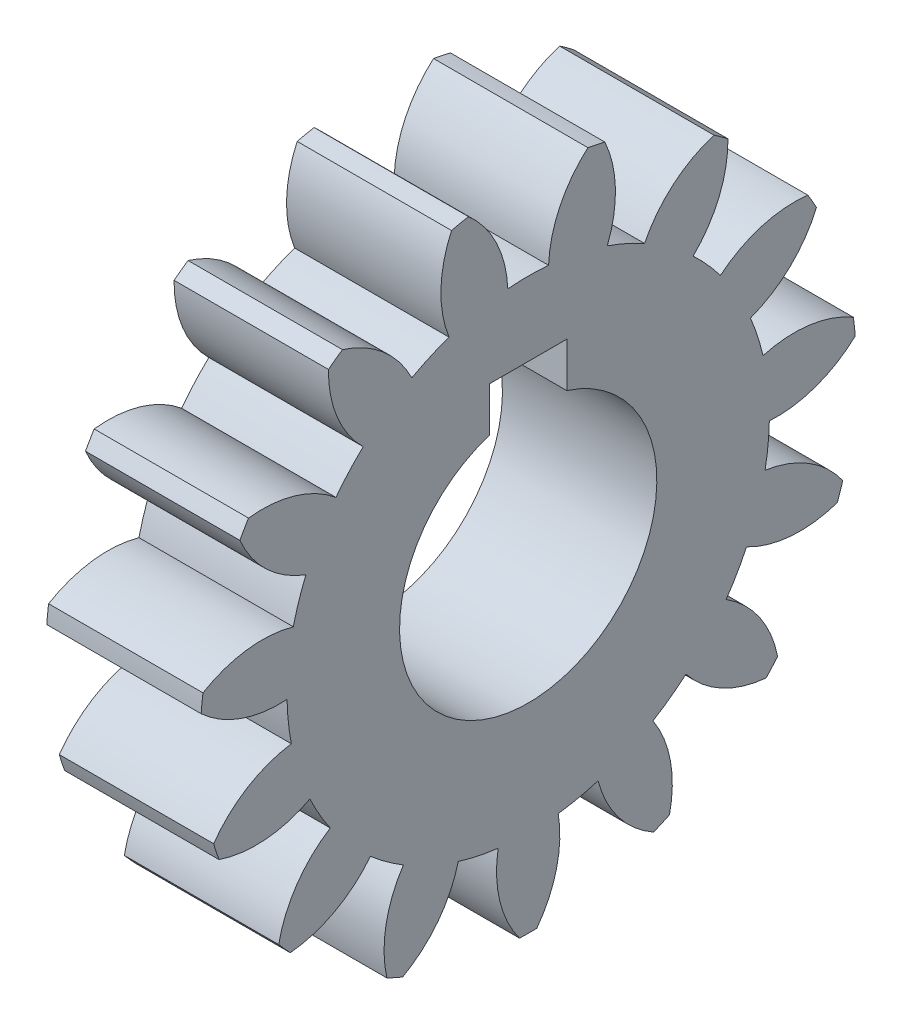
SolidWorks part; units mm, degrees
ref_plane "Plane1" through (0, 0, 0) normal (0, 0, 1) x (1, 0, 0)
ref_plane "Plane2" through (0, 0, 0) normal (0, 1, 0) x (1, 0, 0)
ref_plane "Plane3" through (0, 0, 0) normal (1, 0, 0) x (0, 0, -1)
other "Configuration Table"
sketch "HoldingSke" plane through (0, 0, 0) normal (0, 1, 0) x (1, 0, 0)
  line L0 (0, 0) -> (0.322, -0.0863)
  line L1 (-15, 0) -> (100, 0) construction
  line L2 (0, 0) -> (-2.1039, 2.3779)
  line L3 (0, 0) -> (-11.863, 4.5341)
  line L4 (0, 0) -> (8.3417, 2.2352)
  line L5 (0, 0) -> (-46.8476, -17.4728)
  line L6 (0, 0) -> (-9.9476, -6.7116)
  line L7 (-2.1039, 2.3779) -> (8.6586, 51.2059)
  line L8 (-76.2, 54.61) -> (-73.4, 54.61)
  line L9 (-71.009, 38.7566) -> (-53.1078, 45.2721)
  line L10 (-76.2, 71.12) -> (104.1128, 71.12)
  line L11 (0, 0) -> (-12, 0)
  line L12 (-76.2, 101.6) -> (-76.093, 101.6)
  line L13 (24.9733, 27.94) -> (52.9518, 28.4284)
  line L14 (24.9733, 27.94) -> (24.9743, 27.94)
  line L15 (24.9733, 27.94) -> (100.4006, 29.5858)
  line L16 (-63.627, -3) -> (-12.827, -3)
  circle A0 centre (0, 0) radius 10
  circle A1 centre (0, 0) radius 18.749
  circle A2 centre (0, 0) radius 37.5
  circle A3 centre (0, 0) radius 10
  dimension "MHD" = 37.498
  dimension "Hub_dia" = 75
  dimension "Bore" = 20
  dimension "MBD" = 20
  dimension "Num_teeth" = 15
  dimension "Pitch" = 0.3333
  dimension "Overall_len" = 50
  dimension "Show_teeth" = 15
  dimension "Thickness" = 12
  dimension "OAL" = 50.0001
  dimension "T_dim" = 2.8
  dimension "Ap" = 20
  dimension "H" = 19.05
  dimension "Pitch_radius" = 180.3128
  dimension "Width" = 12
  dimension "Backlash" = 0.107
  dimension "Addendum_fac" = 1
  dimension "Dedendum_fac" = 1.25
  dimension "Clearance_fac" = 0.25
  dimension "Dedendum_add" = 0.001
  dimension "Module" = 3
sketch "BasProSke" plane through (0, 0, 0) normal (0, 1, 0) x (1, 0, 0)
  line L0 (-10, 0) -> (60, 0) construction
  line L1 (0, 0) -> (0, 25.5)
  line L2 (0, 0) -> (12, 0)
  line L3 (12, 0) -> (12, 25.5)
  line L4 (12, 25.5) -> (0, 25.5)
  dimension "Thickness" = 12
  dimension "Diameter" = 51
revolve "Base-Revolve" add sketch "BasProSke" angle 360 about L0
sketch "TooCutSke" plane through (0, 0, 0) normal (1, 0, 0) x (0, 0, -1)
  line L1 (0, 0) -> (0, 107) construction
  line L2 (0, 0) -> (-2.539, 22.3563) construction
  line L3 (0, 0) -> (-9.3126, 43.8125) construction
  line L4 (-2.539, 22.3563) -> (-4.6563, 21.9062) construction
  arc A0 (1.5846, 18.6819) -> (-1.5846, 18.6819) centre (0, 0) ccw
  arc A1 (4.6669, 25.0951) -> (-4.6669, 25.0951) centre (0, 0) ccw
  circle A2 centre (0, 0) radius 22.5 construction
  circle A3 centre (0, 0) radius 21.1431 construction
  arc A4 (-1.5846, 18.6819) -> (-4.6669, 25.0951) centre (-10.5768, 18.3074) ccw
  arc A5 (4.6669, 25.0951) -> (1.5846, 18.6819) centre (10.5768, 18.3074) ccw
  dimension "Root_dia" = 37.498
  dimension "Overcut_dia" = 51.0508
  dimension "Pitch_dia" = 45
  dimension "Base_dia" = 42.2862
  dimension "Flank_rad" = 9
  dimension "Half_ang" = 12
  dimension "Half_CT" = 2.1646
extrude "ToothCut" cut sketch "TooCutSke" along normal through all
fillet "Breaks" [suppressed] radius 0.06
fillet "RootFillets" [suppressed] radius 0.751
pattern_circular "TeethCuts" count 15 every 24 about axis through (-10, 0, 0) along (1, 0, 0) of "ToothCut", "RootFillets", "Breaks"
sketch "HubNeaOneSke" plane through (0, 0, 0) normal (-1, 0, 0) x (0, 0, 1)
  circle A0 centre (0, 0) radius 18.749
  dimension "Diameter" = 37.498
extrude "HubNearOne" [suppressed] add sketch "HubNeaOneSke" along normal blind 38.0001
sketch "HubNeaBotSke" plane through (0, 0, 0) normal (-1, 0, 0) x (0, 0, 1)
  circle A0 centre (0, 0) radius 18.749
  dimension "Diameter" = 37.498
extrude "HubNearBoth" [suppressed] add sketch "HubNeaBotSke" along normal blind 19
ref_plane "FarPln" through (12, 0, 0) normal (1, 0, 0) x (0, 0, -1)
sketch "HubFarSke" plane through (12, 0, 0) normal (1, 0, 0) x (0, 0, -1)
  circle A0 centre (0, 0) radius 18.749
  dimension "Diameter" = 37.498
extrude "HubFar" [suppressed] add sketch "HubFarSke" along normal blind 19
sketch "BorSke" plane through (0, 0, 0) normal (1, 0, 0) x (0, 0, -1)
  circle A0 centre (0, 0) radius 10
  dimension "Diameter" = 20
extrude "Bore" cut sketch "BorSke" along normal mid plane 100.0001
sketch "KeySke" plane through (0, 0, 0) normal (1, 0, 0) x (0, 0, -1)
  line L0 (-3, 0) -> (-3, 12.8)
  line L1 (-3, 12.8) -> (3, 12.8)
  line L2 (3, 12.8) -> (3, 0)
  line L3 (0, 0) -> (0, 34) construction
  line L4 (-3, 0) -> (3, 0)
  dimension "Offset" = 12.8
  dimension "Width" = 6
extrude "Keyway" [suppressed] cut sketch "KeySke" along normal mid plane 100.0001
pattern_circular "Keyway2" [suppressed] count 2 every 90 about axis through (-10, 0, 0) along (1, 0, 0)
sketch "Sketch1" plane through (0, 0, 0) normal (1, 0, 0) x (0, 0, -1)
  line L0 (0, 0) -> (0, 24.1107) construction
  line L2 (-3, 7) -> (3, 7)
  line L3 (-3, 7) -> (-3, 13)
  line L4 (-3, 13) -> (3, 13)
  line L5 (3, 7) -> (3, 13)
  line L6 (-3, 7) -> (3, 13) construction
  line L7 (-3, 13) -> (3, 7) construction
  circle A0 centre (0, 0) radius 10 construction
  point P3 (0, 10)
  dimension "D1" = 6
  dimension "D2" = 6
extrude "Cut-Extrude1" cut sketch "Sketch1" along normal through all both
equation "' \"Module@HoldingSke\" = 6.35"
equation "' \"Num_teeth@HoldingSke\" = 12"
equation "' \"Ap@HoldingSke\" =  20"
equation "' \"Ap@HoldingSke\" = 20"
equation "' \"Width@HoldingSke\" = 0.5 * 25.4"
equation "' \"Hub_dia@HoldingSke\"= 1 * 25.4"
equation "' \"Hub_dia@HoldingSke\" = 1 * 25.4"
equation "' \"Overall_len@HoldingSke\" = 1.0 * 25.4"
equation "' \"Bore@HoldingSke\" = 0.75 * 25.4"
equation "' \"T_dim@HoldingSke\" = 0.1 * 25.4"
equation "' \"Width@KeySke\" = 0.25 * 25.4"
equation "' \"Show_teeth@HoldingSke\" = 13"
equation "' \"Backlash@HoldingSke\" = 0.009 * 25.4"
equation "' \"Addendum_fac@HoldingSke\" = 1.0"
equation "' \"Dedendum_fac@HoldingSke\" = 1.25"
equation "' \"Dedendum_add@HoldingSke\" = 0.00005 * 25.4"
equation "' \"Clearance_fac@HoldingSke\" = 0.25"
equation "\"Pitch@HoldingSke\" = 1 / \"Module@HoldingSke\""
equation "\"Overcut_dia@TooCutSke\" = (\"Num_teeth@HoldingSke\" + 2 * \"Addendum_fac@HoldingSke\") / \"Pitch@HoldingSke\" + 0.002 * 25.4"
equation "\"Pitch_dia@TooCutSke\" = \"Num_teeth@HoldingSke\" / \"Pitch@HoldingSke\""
equation "\"Base_dia@TooCutSke\" = \"Num_teeth@HoldingSke\" / \"Pitch@HoldingSke\" * cos((\"Ap@HoldingSke\"  * 3.14159265 / 180))"
equation "\"Root_dia@TooCutSke\" = (\"Num_teeth@HoldingSke\" + 2) / \"Pitch@HoldingSke\" - 2 * (\"Addendum_fac@HoldingSke\" + \"Dedendum_fac@HoldingSke\") / \"Pitch@HoldingSke\" - \"Dedendum_add@HoldingSke\" * 2"
equation "\"Half_ang@TooCutSke\" = 180 / \"Num_teeth@HoldingSke\""
equation "\"Half_CT@TooCutSke\" = \"Num_teeth@HoldingSke\" / \"Pitch@HoldingSke\" * sin((3.14159265 / 2 / \"Num_teeth@HoldingSke\")) / 2 - 7 * \"Backlash@HoldingSke\" / 4"
equation "\"Flank_rad@TooCutSke\" = \"Num_teeth@HoldingSke\" / \"Pitch@HoldingSke\" / 5"
equation "\"Radius@RootFillets\" = \"Clearance_fac@HoldingSke\" / \"Pitch@HoldingSke\" + \"Dedendum_add@HoldingSke\""
equation "\"Break_rad@Breaks\" = 0.02 / \"Pitch@HoldingSke\""
equation "\"Thickness@HoldingSke\" = \"Width@HoldingSke\""
equation "\"OAL@HoldingSke\" = \"Thickness@HoldingSke\""
equation "\"MHD@HoldingSke\" = (\"Num_teeth@HoldingSke\" + 2) / \"Pitch@HoldingSke\" - 2 * (\"Addendum_fac@HoldingSke\" + \"Dedendum_fac@HoldingSke\")  / \"Pitch@HoldingSke\" - \"Dedendum_add@HoldingSke\" * 2"
equation "\"MBD@HoldingSke\" = (\"Num_teeth@HoldingSke\" + 2) / \"Pitch@HoldingSke\" - 2 * (\"Addendum_fac@HoldingSke\" + \"Dedendum_fac@HoldingSke\")  / \"Pitch@HoldingSke\" - \"Dedendum_add@HoldingSke\" * 2 - 0.002 * 25.4"
equation "\"MHD@HoldingSke\" = ((sgn( \"MHD@HoldingSke\" - \"Hub_dia@HoldingSke\" )-1)*( \"MHD@HoldingSke\" - \"Hub_dia@HoldingSke\" ))/-2+ \"Hub_dia@HoldingSke\""
equation "\"MBD@HoldingSke\" = ((sgn( \"MBD@HoldingSke\" - \"Bore@HoldingSke\" )-1)*( \"MBD@HoldingSke\" - \"Bore@HoldingSke\" ))/-2+ \"Bore@HoldingSke\""
equation "\"OAL@HoldingSke\" = ((sgn( \"OAL@HoldingSke\" - \"Overall_len@HoldingSke\" )+1)*( \"OAL@HoldingSke\" - \"Overall_len@HoldingSke\" ))/2 + \"Overall_len@HoldingSke\" + 0.000002 * 25.4"
equation "\"Num_teeth@TeethCuts\" = int( \"Show_teeth@HoldingSke\" ) + 1"
equation "\"Num_teeth@TeethCuts\" = ((sgn( \"Num_teeth@TeethCuts\" - \"Num_teeth@HoldingSke\" )-1)*( \"Num_teeth@TeethCuts\" - \"Num_teeth@HoldingSke\" ))/-2+ \"Num_teeth@HoldingSke\""
equation "\"Num_teeth@TeethCuts\" = ((sgn( \"Num_teeth@TeethCuts\" - 2.0)+1)*( \"Num_teeth@TeethCuts\" - 2.0))/2 +2.0"
equation "\"Angle@TeethCuts\" = 360.0 / \"Num_teeth@HoldingSke\""
equation "\"Diameter@BasProSke\" = (\"Num_teeth@HoldingSke\" + 2 * \"Addendum_fac@HoldingSke\") / \"Pitch@HoldingSke\""
equation "\"Thickness@BasProSke\"  = \"Thickness@HoldingSke\""
equation "' \"Fillet_rad@BasProSke\" =  \"Thickness@HoldingSke\" * 0.05"
equation "' \"Fillet_rad@BasProSke\" = \"Thickness@HoldingSke\" * 0.05"
equation "\"MHD@HoldingSke\" = ((sgn( \"MHD@HoldingSke\" - \"Root_dia@TooCutSke\" )-1)*( \"MHD@HoldingSke\" - \"Root_dia@TooCutSke\" ))/-2+ \"Root_dia@TooCutSke\""
equation "\"Diameter@HubNeaOneSke\" = \"MHD@HoldingSke\""
equation "\"Length@HubNearOne\" = \"OAL@HoldingSke\" - \"Thickness@BasProSke\""
equation "\"Diameter@HubNeaBotSke\" = \"MHD@HoldingSke\""
equation "\"Length@HubNearBoth\" = ( \"OAL@HoldingSke\" - \"Thickness@BasProSke\" ) / 2.0"
equation "\"Thickness@FarPln\" = \"Thickness@BasProSke\""
equation "\"Diameter@HubFarSke\" = \"MHD@HoldingSke\""
equation "\"Length@HubFar\" = ( \"OAL@HoldingSke\" - \"Thickness@BasProSke\" ) / 2.0"
equation "\"Diameter@BorSke\" = \"MBD@HoldingSke\""
equation "\"D1@Bore\" = \"OAL@HoldingSke\" * 2.0"
equation "\"D1@Keyway\" = \"OAL@HoldingSke\" * 2.0"
equation "\"Offset@KeySke\" = \"T_dim@HoldingSke\" + \"MBD@HoldingSke\" / 2.0"
